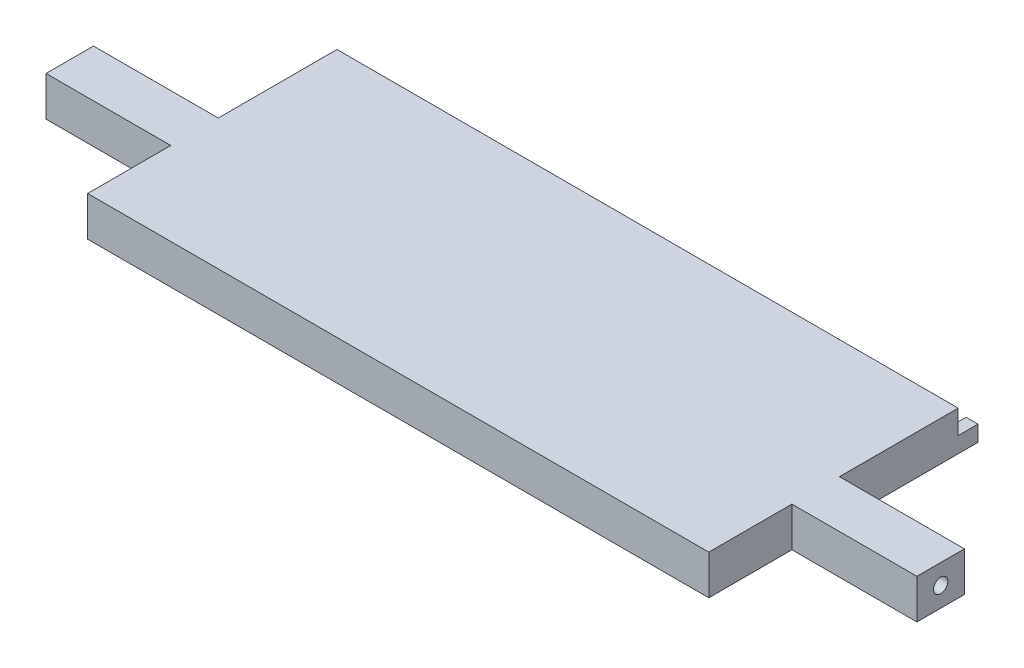
SolidWorks part; units mm, degrees
ref_plane "Спереди" through (0, 0, 0) normal (0, 0, 1) x (1, 0, 0)
ref_plane "Сверху" through (0, 0, 0) normal (0, 1, 0) x (1, 0, 0)
ref_plane "Справа" through (0, 0, 0) normal (1, 0, 0) x (0, 0, -1)
sketch "Эскиз1" plane through (0, 0, 0) normal (0, 0, 1) x (1, 0, 0)
  line L0 (-1000, 5) -> (49000, 5) construction
  line L1 (0, 0) -> (220, 0)
  line L2 (0, 0) -> (0, 10)
  line L3 (0, 10) -> (220, 10)
  line L4 (220, 0) -> (220, 10)
  circle A0 centre (37.97, 5) radius 3.6
  circle A9 centre (55.97, 5) radius 3.6
  circle A10 centre (73.97, 5) radius 3.6
  circle A11 centre (91.97, 5) radius 3.6
  circle A12 centre (109.97, 5) radius 3.6
  circle A13 centre (127.97, 5) radius 3.6
  circle A14 centre (145.97, 5) radius 3.6
  circle A15 centre (163.97, 5) radius 3.6
  circle A16 centre (181.97, 5) radius 3.6
  point P26 (0, 5)
  dimension "D3" = 7.2
  dimension "D6" = 38.03
  dimension "D7" = 10.8
  dimension "D8" = 18
  dimension "D1" = 5
  dimension "D2" = 220
  dimension "D4" = 37.97
  dimension "D5" = 9
extrude "Бобышка-Вытянуть1" add sketch "Эскиз1" along normal blind 65
sketch "Эскиз2" plane through (0, 10, 0) normal (0, 1, 0) x (1, 0, 0)
  line L0 (220, -65) -> (220, 0) construction
  line L1 (0, 0) -> (220, 0)
  line L2 (0, 0) -> (0, -5)
  line L3 (0, -5) -> (220, -5)
  line L4 (220, 0) -> (220, -5)
  dimension "D1" = 5
extrude "Вырез-Вытянуть1" cut sketch "Эскиз2" against normal blind 6
sketch "Эскиз3" plane through (0, 10, 0) normal (0, 1, 0) x (1, 0, 0)
  line L0 (220, -65) -> (0, -65) construction
  line L1 (0, 0) -> (31.5117, 0)
  line L2 (0, 0) -> (0, -35)
  line L3 (0, -35) -> (31.5117, -35)
  line L4 (31.5117, 0) -> (31.5117, -35)
  line L5 (0, -65) -> (31.5117, -65)
  line L6 (0, -65) -> (0, -47)
  line L7 (0, -47) -> (31.5117, -47)
  line L8 (31.5117, -65) -> (31.5117, -47)
  line L9 (185.4283, -5) -> (185.4283, 0) construction
  line L10 (220, 0) -> (188.4283, 0)
  line L11 (220, 0) -> (220, -35)
  line L12 (220, -35) -> (188.4283, -35)
  line L13 (188.4283, 0) -> (188.4283, -35)
  line L14 (220, -65) -> (188.4283, -65)
  line L15 (220, -65) -> (220, -47)
  line L16 (220, -47) -> (188.4283, -47)
  line L17 (188.4283, -65) -> (188.4283, -47)
  line L18 (34.5117, 0) -> (34.5117, -5) construction
  dimension "D1" = 12
  dimension "D2" = 12
  dimension "D3" = 18
  dimension "D4" = 18
  dimension "D5" = 3
  dimension "D6" = 3
  dimension "D7" = 3
  dimension "D8" = 3
extrude "Вырез-Вытянуть2" cut sketch "Эскиз3" against normal through all
sketch "Эскиз4" plane through (0, 0, 0) normal (-1, 0, 0) x (0, 0, 1)
  line L3 (47, 0) -> (35, 0) construction
  line L4 (35, 0) -> (35, 10) construction
  circle A0 centre (41, 5) radius 1.8
  dimension "D1" = 3.6
  dimension "D2" = 6
  dimension "D3" = 5
extrude "Вырез-Вытянуть3" cut sketch "Эскиз4" against normal blind 10
sketch "Эскиз5" plane through (220, 0, 0) normal (1, 0, 0) x (0, 0, -1)
  line L1 (-47, 0) -> (-47, 10) construction
  line L2 (-47, 0) -> (-35, 0) construction
  circle A0 centre (-41, 5) radius 1.8
  dimension "D1" = 3.6
  dimension "D2" = 5
  dimension "D3" = 6
extrude "Вырез-Вытянуть4" cut sketch "Эскиз5" against normal blind 10
sketch "Эскиз6" plane through (0, 0, 65) normal (0, 0, 1) x (1, 0, 0)
  line L1 (31.5117, 10) -> (188.4283, 10)
  line L2 (31.5117, 10) -> (31.5117, 0)
  line L3 (31.5117, 0) -> (188.4283, 0)
  line L4 (188.4283, 10) -> (188.4283, 0)
extrude "Бобышка-Вытянуть2" add sketch "Эскиз6" along normal blind 3
